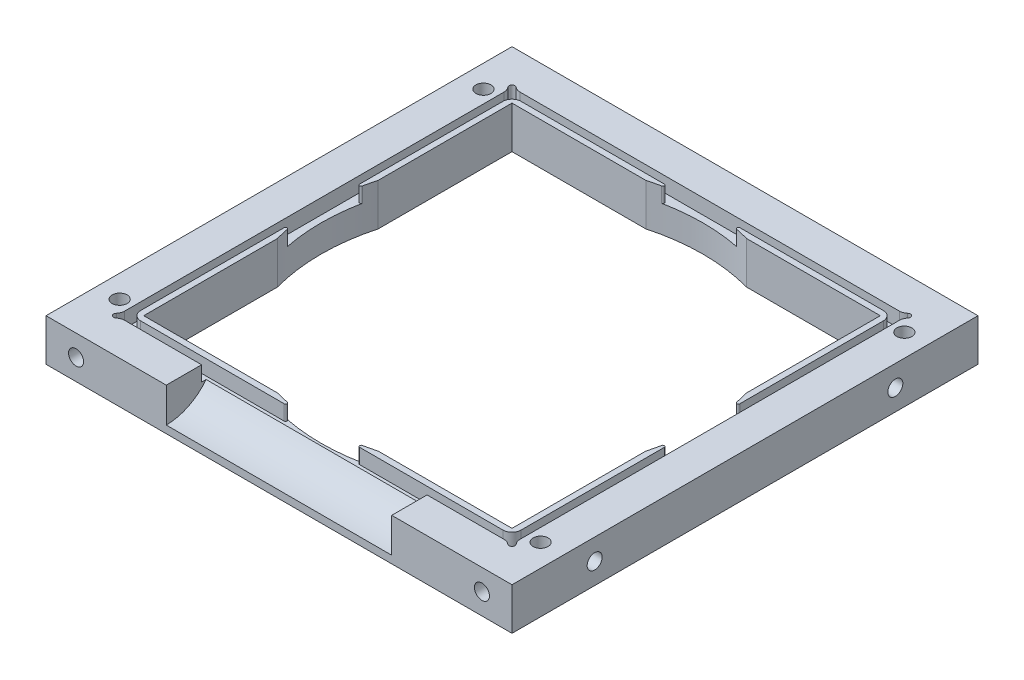
SolidWorks part; units mm, degrees
ref_plane "Front" through (0, 0, 0) normal (0, 0, 1) x (1, 0, 0)
ref_plane "Top" through (0, 0, 0) normal (0, 1, 0) x (1, 0, 0)
ref_plane "Right" through (0, 0, 0) normal (1, 0, 0) x (0, 0, -1)
sketch "Sketch1" plane through (0, 0, 0) normal (0, 1, 0) x (1, 0, 0)
  line L1 (-77.5, -77.5) -> (77.5, -77.5)
  line L2 (-77.5, -77.5) -> (-77.5, 77.5)
  line L3 (-77.5, 77.5) -> (77.5, 77.5)
  line L4 (77.5, -77.5) -> (77.5, 77.5)
  line L5 (-77.5, -77.5) -> (77.5, 77.5) construction
  line L6 (-77.5, 77.5) -> (77.5, -77.5) construction
  point P0 (0, 0)
  point P8 (0, -77.5)
  dimension "D3" = 155
extrude "Boss-Extrude1" add sketch "Sketch1" along normal blind 14
sketch "Sketch2" plane through (0, 14, 0) normal (0, 1, 0) x (1, 0, 0)
  line L0 (-65.75, -65.75) -> (-65.75, 65.75)
  line L5 (-65.75, 65.75) -> (65.75, 65.75)
  line L6 (65.75, 65.75) -> (65.75, -65.75)
  line L11 (65.75, -65.75) -> (-65.75, -65.75)
  line L12 (-63.25, -63.25) -> (63.25, -63.25)
  line L13 (63.25, -63.25) -> (63.25, 63.25)
  line L14 (63.25, 63.25) -> (-63.25, 63.25)
  line L15 (-63.25, 63.25) -> (-63.25, -63.25)
  line L20 (0, -65.75) -> (0, -77.5) construction
  line L21 (-77.5, -77.5) -> (77.5, -77.5) construction
  line L22 (0, 65.75) -> (0, 77.5) construction
  line L23 (77.5, 77.5) -> (-77.5, 77.5) construction
  line L24 (-63.25, 63.25) -> (-65.75, 63.25) construction
  line L25 (-63.25, 63.25) -> (-63.25, 65.75) construction
  point P8 (0, 65.75)
  point P10 (0, 63.25)
  point P11 (0, -63.25)
  point P12 (0, -65.75)
  dimension "D2" = 126.5
  dimension "D5" = 2.5
extrude "Cut-Extrude1" cut sketch "Sketch2" against normal blind 5
sketch "Sketch3" plane through (0, 14, 0) normal (0, 1, 0) x (1, 0, 0)
  line L8 (-61.25, 61.25) -> (-61.25, -61.25)
  line L9 (-61.25, -61.25) -> (61.25, -61.25)
  line L10 (61.25, -61.25) -> (61.25, 61.25)
  line L11 (61.25, 61.25) -> (-61.25, 61.25)
  line L12 (-61.25, 61.25) -> (-61.25, -61.25)
  line L13 (-61.25, -61.25) -> (61.25, -61.25)
  line L14 (61.25, -61.25) -> (61.25, 61.25)
  line L15 (61.25, 61.25) -> (-61.25, 61.25)
  dimension "D1" = 2
extrude "Cut-Extrude2" cut sketch "Sketch3" against normal through all
sketch "Sketch6" plane through (0, 0, 77.5) normal (0, 0, 1) x (1, 0, 0)
  line L0 (67.5, 7) -> (-67.5, 7) construction
  line L1 (0, 0) -> (0, 14) construction
  line L2 (-77.5, 0) -> (77.5, 0) construction
  line L3 (-77.5, 14) -> (77.5, 14) construction
  circle A0 centre (67.5, 7) radius 2.5
  circle A1 centre (-67.5, 7) radius 2.5
  point P10 (0, 7)
  point P11 (0, 7)
  dimension "D2" = 5
  dimension "D1" = 135
extrude "Cut-Extrude5" cut sketch "Sketch6" against normal blind 11
sketch "Sketch7" plane through (0, 0, 0) normal (0, -1, 0) x (1, 0, 0)
  line L0 (70, 60.5) -> (70, -60.5) construction
  line L1 (70, -60.5) -> (-70, -60.5) construction
  line L2 (-70, -60.5) -> (-70, 60.5) construction
  line L3 (-70, 60.5) -> (70, 60.5) construction
  line L4 (77.5, 77.5) -> (77.5, -77.5) construction
  line L6 (-77.5, 77.5) -> (77.5, 77.5) construction
  circle A0 centre (70, -60.5) radius 2.5
  circle A1 centre (70, 60.5) radius 2.5
  circle A2 centre (-70, 60.5) radius 2.5
  circle A3 centre (-70, -60.5) radius 2.5
  point P8 (70, 0)
  point P9 (0, -60.5)
  dimension "D1" = 5
  dimension "D2" = 7.5
  dimension "D3" = 17
extrude "Cut-Extrude6" cut sketch "Sketch7" against normal through all
sketch "Sketch8" plane through (0, 0, 77.5) normal (0, 0, 1) x (1, 0, 0)
  line L0 (-77.5, 14) -> (77.5, 14) construction
  line L1 (37.5, 14) -> (-37.5, 14)
  line L2 (37.5, 14) -> (37.5, 0)
  line L3 (37.5, 0) -> (-37.5, 0)
  line L4 (-37.5, 14) -> (-37.5, 0)
  line L5 (-77.5, 0) -> (77.5, 0) construction
  point P8 (0, 0)
  dimension "D1" = 75
extrude "Cut-Extrude7" cut sketch "Sketch8" against normal offset from surface (13.25 mm away) 1 up to face at (0, 11.5, 63.25)
sketch "Sketch9" plane through (0, 14, 0) normal (0, 1, 0) x (1, 0, 0)
  line L0 (37.5, -65.75) -> (65.75, -65.75) construction
  line L1 (37.5, -65.75) -> (65.75, -65.75) construction
  circle A0 centre (-65.75, 65.75) radius 1
  circle A1 centre (65.75, 65.75) radius 1
  circle A2 centre (65.75, -65.75) radius 1
  circle A3 centre (-65.75, -65.75) radius 1
  dimension "D1" = 2
extrude "Cut-Extrude8" cut sketch "Sketch9" against normal up to surface (5 mm away)
fillet "Fillet1" radius 3 12 edges at (-64.75, 11.5, 65.75) (-63.25, 11.5, 63.25) (-65.75, 11.5, 64.75) (-65.75, 11.5, -64.75) (-63.25, 11.5, -63.25) (-64.75, 11.5, -65.75) (65.75, 11.5, -64.75) (63.25, 11.5, -63.25) (64.75, 11.5, -65.75) (64.75, 11.5, 65.75) (65.75, 11.5, 64.75) (63.25, 11.5, 63.25)
sketch "Sketch10" plane through (77.5, 0, 0) normal (1, 0, 0) x (0, 0, -1)
  line L0 (0, 0) -> (0, 14) construction
  line L1 (-77.5, 0) -> (77.5, 0) construction
  line L2 (-77.5, 14) -> (77.5, 14) construction
  line L3 (50, 7) -> (-50, 7) construction
  circle A0 centre (50, 7) radius 2.5
  circle A1 centre (-50, 7) radius 2.5
  point P12 (0, 7)
  point P13 (0, 7)
  dimension "D1" = 5
  dimension "D2" = 100
extrude "Cut-Extrude9" cut sketch "Sketch10" against normal blind 10
sketch "Sketch12" plane through (37.5, 0, 0) normal (-1, 0, 0) x (0, 0, 1)
  line L0 (77.5, 0) -> (77.5, 14) construction
  line L1 (77.5, 2.5) -> (77.5, 0)
  line L2 (77.5, 0) -> (64.25, 0)
  line L3 (64.25, 0) -> (64.25, 9)
  arc A0 (77.5, 2.5) -> (64.25, 9) centre (77.5, 19.2548) cw
  point P3 (0, 0)
  dimension "D1" = 2.5
extrude "Boss-Extrude2" add sketch "Sketch12" along normal up to surface (75 mm away) up to face at (-37.5, 7.6667, 69.1667)
sketch "Sketch11" plane through (0, 14, 0) normal (0, 1, 0) x (1, 0, 0)
  circle A0 centre (0, 0) radius 63.5
  dimension "D1" = 127
extrude "Cut-Extrude10" cut sketch "Sketch11" against normal through all
fillet "Fillet2" radius 0.5 8 edges at (5.6292, 11.5, 63.25) (-5.6292, 11.5, 63.25) (63.25, 11.5, 5.6292) (63.25, 11.5, -5.6292) (5.6292, 11.5, -63.25) (-5.6292, 11.5, -63.25) (-63.25, 11.5, -5.6292) (-63.25, 11.5, 5.6292)
